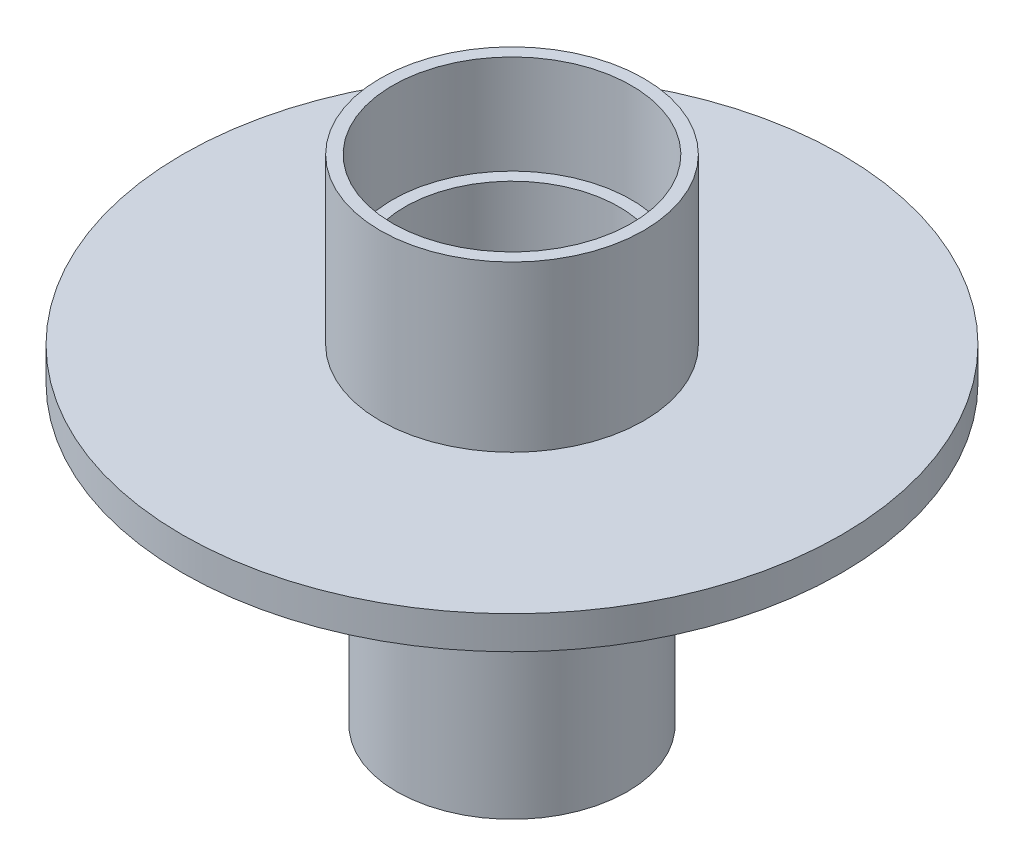
SolidWorks part; units mm, degrees
ref_plane "Front Plane" through (0, 0, 0) normal (0, 0, 1) x (1, 0, 0)
ref_plane "Top Plane" through (0, 0, 0) normal (0, 1, 0) x (1, 0, 0)
ref_plane "Right Plane" through (0, 0, 0) normal (1, 0, 0) x (0, 0, -1)
sketch "Sketch1" plane through (0, 0, 0) normal (1, 0, 0) x (0, 0, -1)
  line L0 (0, 28.0586) -> (0, -24.3494) construction
  line L5 (-16, 3.3739) -> (-40, 3.3739)
  line L6 (-40, 3.3739) -> (-40, -0.6261)
  line L7 (-40, -0.6261) -> (-14.5, -0.6261)
  line L8 (-13, -0.6261) -> (-13, 11.3739)
  line L14 (-16, 3.3739) -> (-16, 23.3739)
  line L15 (-16, 23.3739) -> (-14.5, 23.3739)
  line L16 (-14.5, 23.3739) -> (-14.5, 11.3739)
  line L17 (-13, 11.3739) -> (-14.5, 11.3739)
  line L19 (-14, -36.6261) -> (-13, -36.6261)
  line L20 (-13, -36.6261) -> (-13, -0.6261)
  line L21 (-14, -0.6261) -> (-14, -36.6261)
  line L22 (-14.5, -0.6261) -> (-14, -0.6261)
  dimension "D1" = 29
  dimension "D3" = 12
  dimension "D4" = 1.5
  dimension "D5" = 4
  dimension "D6" = 28
  dimension "D7" = 80
  dimension "D9" = 36
revolve "Revolve1" add sketch "Sketch1" angle 360 about L0
ref_plane "Plane1" through (0, 13.3739, 0) normal (0, 1, 0) x (1, 0, 0)
